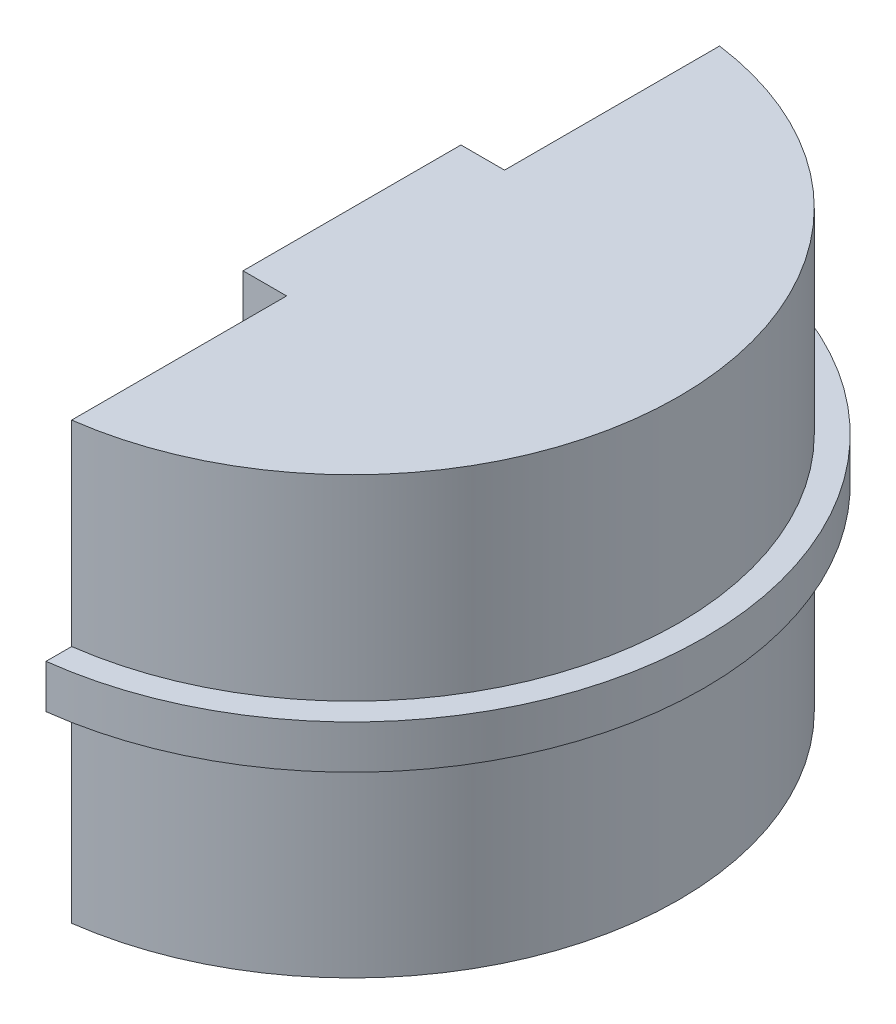
SolidWorks part; units mm, degrees
ref_plane "Front Plane" through (0, 0, 0) normal (0, 0, 1) x (1, 0, 0)
ref_plane "Top Plane" through (0, 0, 0) normal (0, 1, 0) x (1, 0, 0)
ref_plane "Right Plane" through (0, 0, 0) normal (1, 0, 0) x (0, 0, -1)
sketch "Sketch1" plane through (0, 0, 0) normal (0, 1, 0) x (1, 0, 0)
  line L0 (-113.8613, 23.4264) -> (-103.8613, 23.4264)
  line L1 (-103.8613, 23.4264) -> (-103.8613, 72.7567)
  line L2 (-113.8613, -26.5736) -> (-103.8613, -26.5736)
  line L3 (-103.8613, -26.5736) -> (-103.8613, -75.9039)
  line L7 (-113.8613, 23.4264) -> (-113.8613, -26.5736)
  arc A0 (-103.8613, -75.9039) -> (-103.8613, 72.7567) centre (-113.8613, -1.5736) ccw
extrude "Boss-Extrude1" add sketch "Sketch1" along normal blind 100
ref_plane "Plane1" through (0, 50, 0) normal (0, 1, 0) x (1, 0, 0)
sketch "Sketch2" plane through (0, 50, 0) normal (0, 1, 0) x (1, 0, 0)
  line L0 (-113.8613, 23.4264) -> (-113.8613, -26.5736) construction
  line L6 (-103.8613, -75.9039) -> (-103.8613, -81.7875)
  line L7 (-103.8613, 72.7567) -> (-103.8613, 78.6403)
  arc A0 (-103.8613, -75.9039) -> (-103.8613, 72.7567) centre (-113.8613, -1.5736) ccw
  arc A1 (-103.8613, -81.7875) -> (-103.8613, 78.6403) centre (-113.8613, -1.5736) ccw
extrude "Boss-Extrude2" add sketch "Sketch2" along normal mid plane 10
